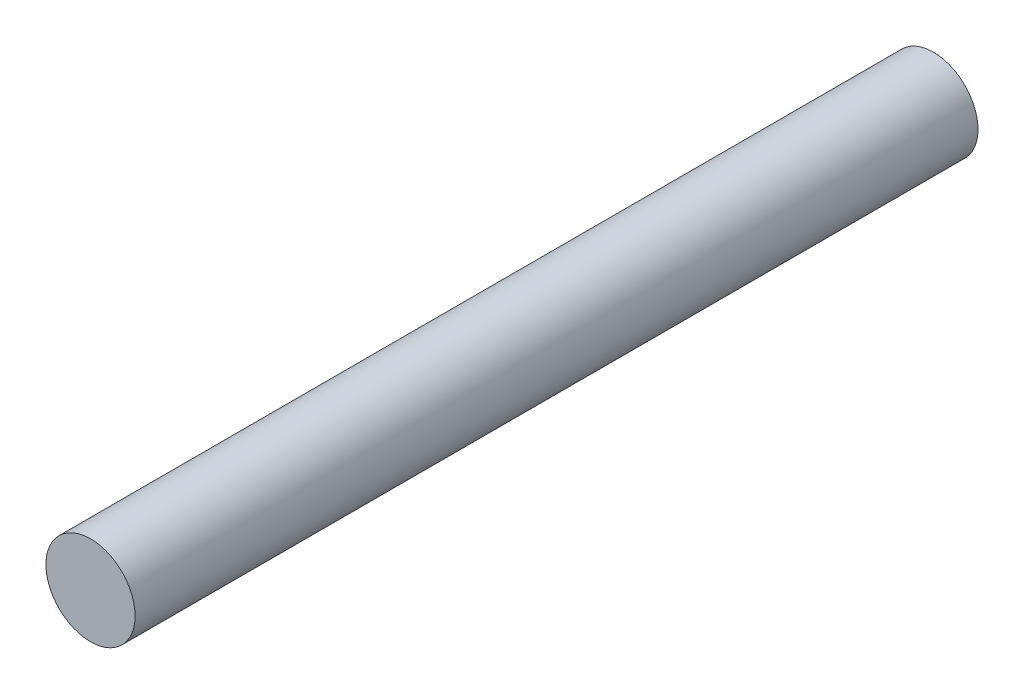
SolidWorks part; units mm, degrees
ref_plane "Front Plane" through (0, 0, 0) normal (0, 0, 1) x (1, 0, 0)
ref_plane "Top Plane" through (0, 0, 0) normal (0, 1, 0) x (1, 0, 0)
ref_plane "Right Plane" through (0, 0, 0) normal (1, 0, 0) x (0, 0, -1)
sketch "Sketch2" plane through (0, 0, 0) normal (0, 0, 1) x (1, 0, 0)
  circle A0 centre (0, 0) radius 12.7
  dimension "D1" = 25.4
extrude "Boss-Extrude1" add sketch "Sketch2" along normal mid plane 240
